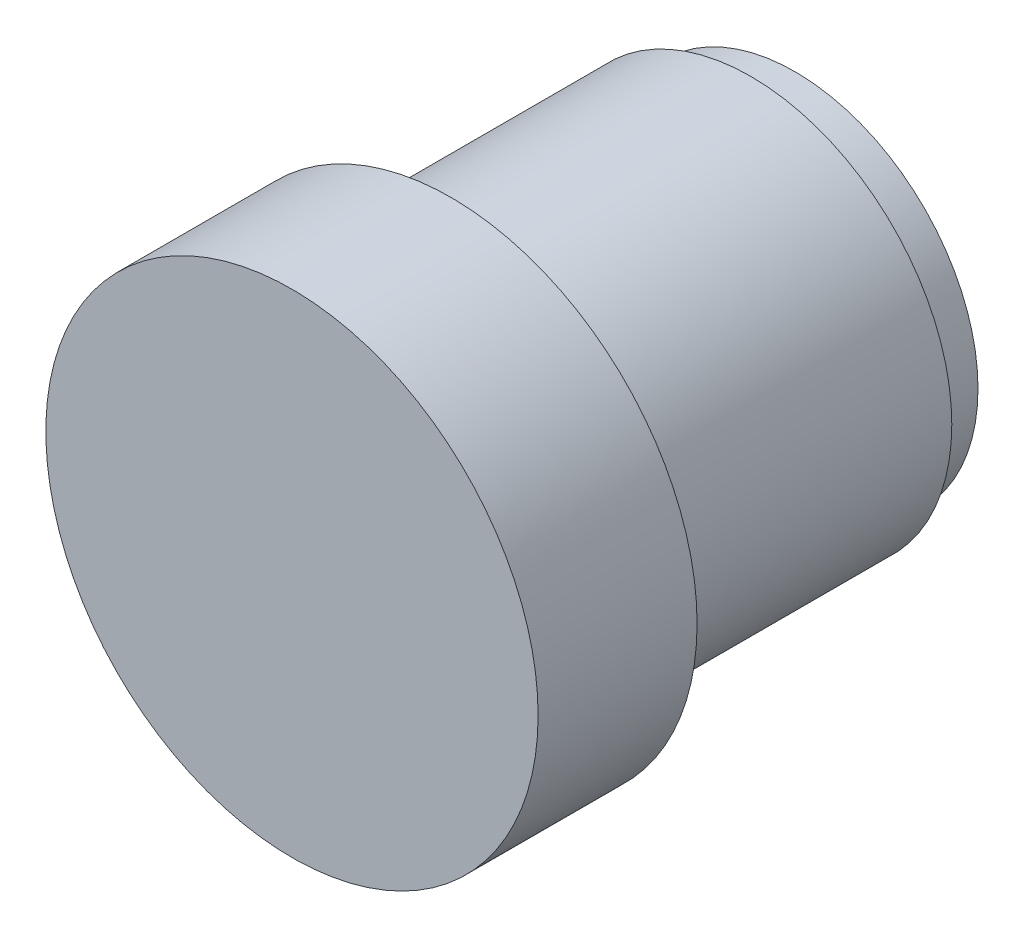
SolidWorks part; units mm, degrees
ref_plane "Front Plane" through (0, 0, 0) normal (0, 0, 1) x (1, 0, 0)
ref_plane "Top Plane" through (0, 0, 0) normal (0, 1, 0) x (1, 0, 0)
ref_plane "Right Plane" through (0, 0, 0) normal (1, 0, 0) x (0, 0, -1)
sketch "Sketch1" plane through (0, 0, 0) normal (0, 0, 1) x (1, 0, 0)
  circle A0 centre (0, 0) radius 20.25
extrude "Boss-Extrude1" add sketch "Sketch1" along normal blind 4.9
sketch "Sketch2" plane through (0, 0, 4.9) normal (0, 0, 1) x (1, 0, 0)
  circle A0 centre (0, 0) radius 22.25
extrude "Boss-Extrude2" add sketch "Sketch2" along normal blind 33.2
sketch "Sketch4" plane through (0, 0, 0) normal (0, 0, -1) x (-1, 0, 0)
  circle A2 centre (0, 0) radius 19.25
extrude "Cut-Extrude2" cut sketch "Sketch4" against normal blind 58.2
sketch "Sketch5" plane through (0, 0, 38.1) normal (0, 0, 1) x (1, 0, 0)
  circle A0 centre (0, 0) radius 27.25
extrude "Boss-Extrude3" add sketch "Sketch5" along normal blind 17.6
